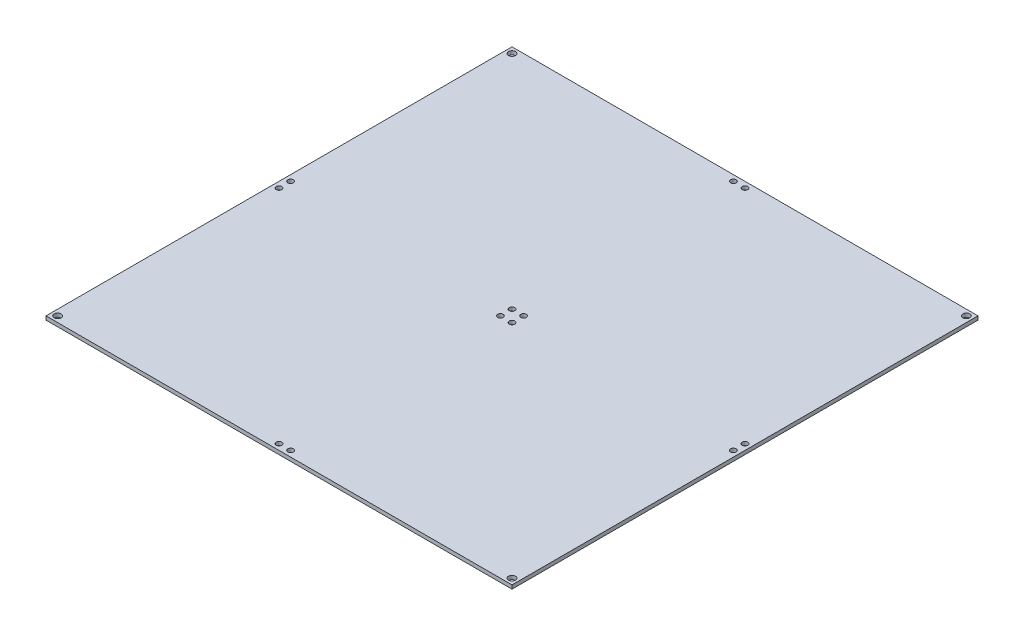
SolidWorks part; units mm, degrees
ref_plane "Front Plane" through (0, 0, 0) normal (0, 0, 1) x (1, 0, 0)
ref_plane "Top Plane" through (0, 0, 0) normal (0, 1, 0) x (1, 0, 0)
ref_plane "Right Plane" through (0, 0, 0) normal (1, 0, 0) x (0, 0, -1)
sketch "Sketch1" plane through (0, 0, 0) normal (0, 1, 0) x (1, 0, 0)
  line L0 (0, 0) -> (0, 127.071) construction
  line L1 (-100, -100) -> (100, -100)
  line L2 (-100, -100) -> (-100, 100)
  line L3 (-100, 100) -> (100, 100)
  line L4 (100, -100) -> (100, 100)
  line L5 (-100, -100) -> (100, 100) construction
  line L6 (-100, 100) -> (100, -100) construction
  line L7 (0, 0) -> (-148.4613, 0) construction
  circle A0 centre (-97.5, 97.5) radius 1.5
  circle A1 centre (97.5, 97.5) radius 1.5
  circle A2 centre (-97.5, -97.5) radius 1.5
  circle A3 centre (97.5, -97.5) radius 1.5
  point P0 (0, 0)
  dimension "D3" = 3
  dimension "D1" = 200
  dimension "D2" = 200
  dimension "D4" = 2.5
  dimension "D5" = 2.5
extrude "Boss-Extrude2" add sketch "Sketch1" along normal blind 1.6
hole_wizard "3/32 (0.09375) Diameter Hole1" positions "Sketch9" profile "Sketch8" hole size "3/32" standard "ANSI Inch" end condition through all
sketch "Sketch9" plane through (0, 1.6, 0) normal (0, 1, 0) x (1, 0, 0)
  point P0 (2.5, -97.5)
  point P3 (-2.5, -97.5)
  point P6 (2.5, -2.5)
  point P9 (-2.5, -2.5)
  point P12 (-2.5, 2.5)
  point P15 (2.5, 2.5)
  point P18 (-97.5, -2.5)
  point P21 (-97.5, 2.5)
  point P24 (97.5, -2.5)
  point P27 (97.5, 2.5)
  point P30 (2.5, 97.5)
  point P33 (-2.5, 97.5)
sketch "Sketch8" plane through (2.5, 1.6, 97.5) normal (1, 0, 0) x (0, 0, 1)
  line L0 (0, 0) -> (0, 1.6)
  line L1 (0, 1.6) -> (1.1906, 1.6)
  line L2 (1.1906, 1.6) -> (1.1906, 0)
  line L5 (1.1906, 0) -> (0, 0)
  line L11 (0, -6.35) -> (0, 107.95) construction
  dimension "Thru Hole Dia." = 2.3812
  dimension "Thru Hole Depth" = 1.6
